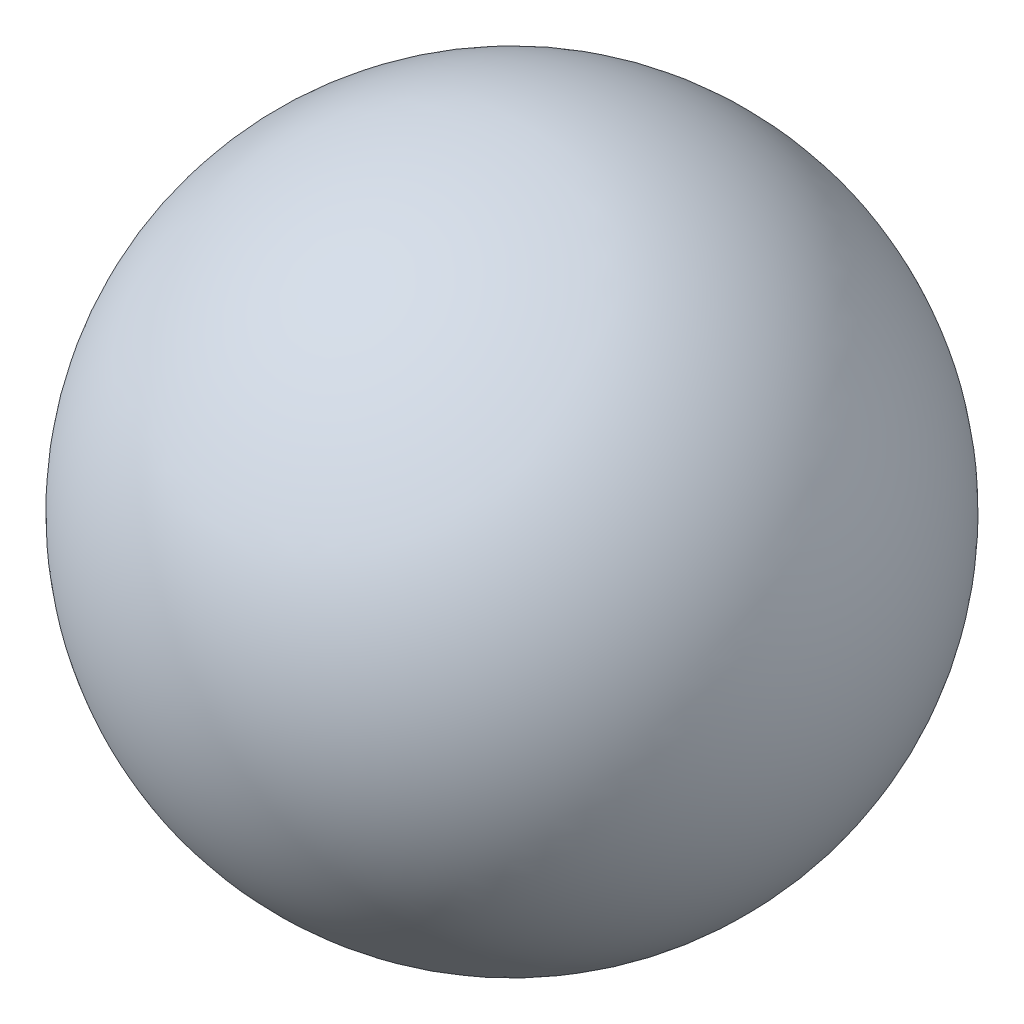
SolidWorks part; units mm, degrees
material "ABS"
ref_plane "Спереди" through (0, 0, 0) normal (0, 0, 1) x (1, 0, 0)
ref_plane "Сверху" through (0, 0, 0) normal (0, 1, 0) x (1, 0, 0)
ref_plane "Справа" through (0, 0, 0) normal (1, 0, 0) x (0, 0, -1)
other "Configuration Table"
sketch "Эскиз1" plane through (0, 0, 0) normal (0, 1, 0) x (1, 0, 0)
  line L0 (0, 100) -> (0, -100) construction
  line L1 (0, 100) -> (0, 94.2)
  line L2 (0, -94.2) -> (0, -100)
  arc A1 (0, 100) -> (0, -100) centre (0, 0) cw
  arc A2 (0, 94.2) -> (0, -94.2) centre (0, 0) cw
  dimension "D1" = 100
  dimension "D2" = 5.8
revolve "Повернуть1" add sketch "Эскиз1" angle 360 about L0
sketch "Эскиз3" plane through (0, 0, 0) normal (0, 0, 1) x (1, 0, 0)
  line L0 (0, 100) -> (0, -100) construction
  line L1 (99.4987, -10) -> (-99.4987, -10) construction
  circle A0 centre (0, 0) radius 100 construction
  point P5 (0, -10)
  dimension "D1" = 90
